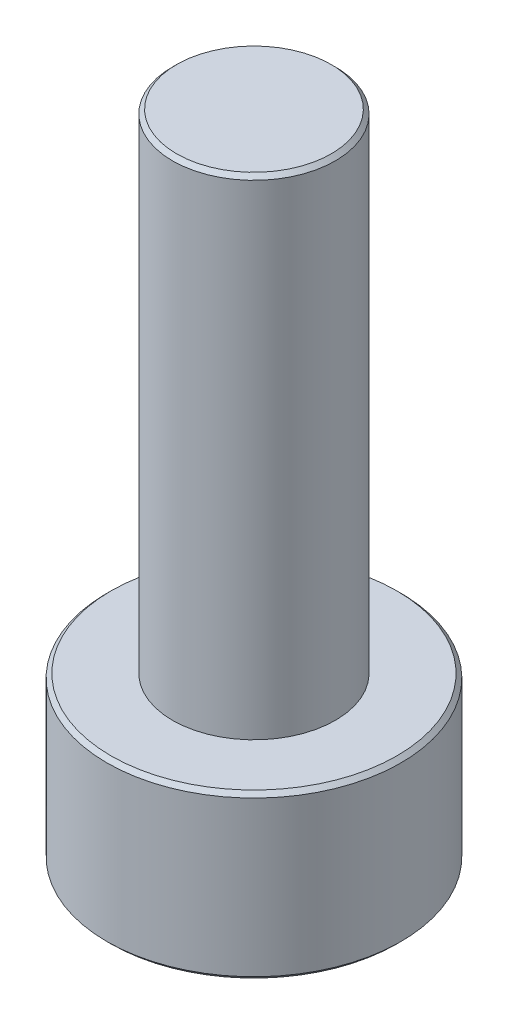
SolidWorks part; units mm, degrees
material "Q235"
ref_plane "前视基准面" through (0, 0, 0) normal (0, 0, 1) x (1, 0, 0)
ref_plane "上视基准面" through (0, 0, 0) normal (0, 1, 0) x (1, 0, 0)
ref_plane "右视基准面" through (0, 0, 0) normal (1, 0, 0) x (0, 0, -1)
sketch "草图1" plane through (0, 0, 0) normal (0, 1, 0) x (1, 0, 0)
  circle A0 centre (0, 0) radius 3.61
  dimension "D1" = 7.22
extrude "杯头部分" add sketch "草图1" along normal blind 4
sketch "草图2" plane through (0, 4, 0) normal (0, 1, 0) x (1, 0, 0)
  circle A0 centre (0, 0) radius 2
  dimension "D1" = 4
extrude "螺柱部分" add sketch "草图2" along normal blind 12
cosmetic thread "装饰螺纹线1" parameters "D2"=2.459
sketch "草图3" plane through (0, 0, 0) normal (0, -1, 0) x (1, 0, 0)
  line L1 (1.54, -0.8891) -> (1.54, 0.8891)
  line L2 (1.54, 0.8891) -> (0, 1.7782)
  line L3 (0, 1.7782) -> (-1.54, 0.8891)
  line L4 (-1.54, 0.8891) -> (-1.54, -0.8891)
  line L5 (-1.54, -0.8891) -> (0, -1.7782)
  line L6 (0, -1.7782) -> (1.54, -0.8891)
  circle A0 centre (0, 0) radius 1.54 construction
  dimension "D1" = 3.08
extrude "沉头内六角" cut sketch "草图3" against normal blind 2
chamfer "修饰性倒角" distance 0.1 angle 45 3 edges at (0, 16, 2) (0, 4, 3.61) (0, 0, 3.61)
